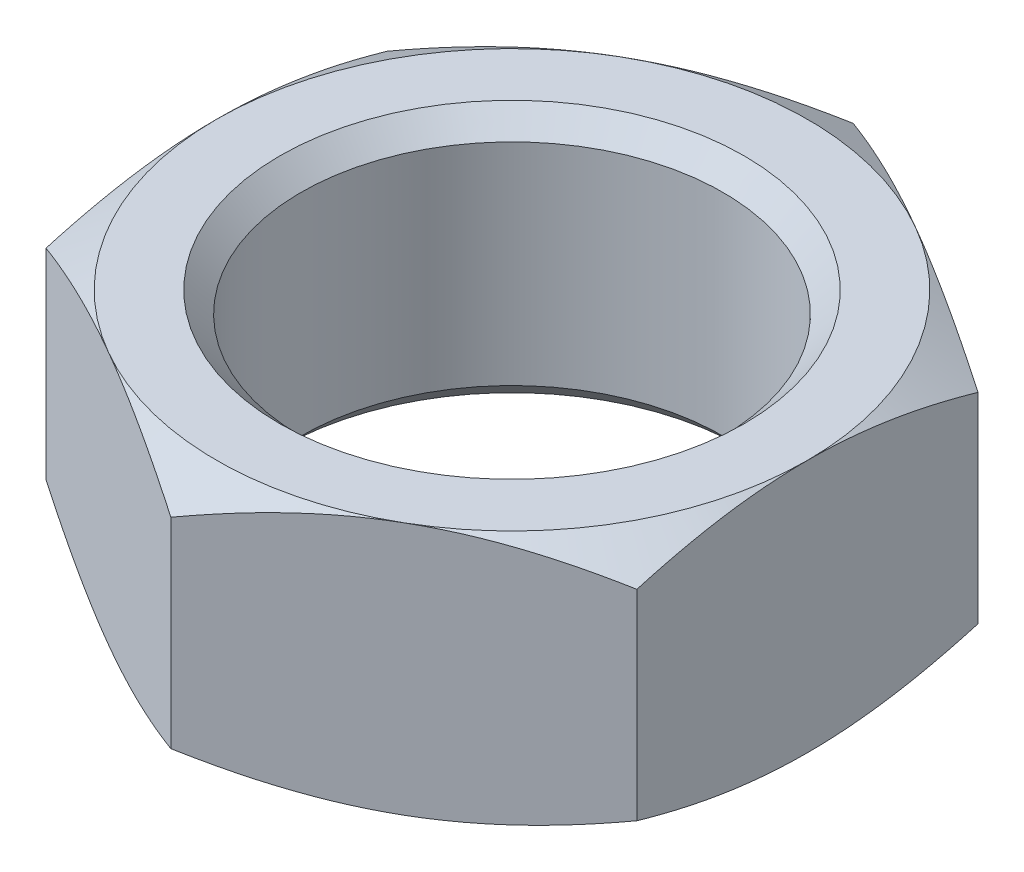
SolidWorks part; units mm, degrees
ref_plane "Front Plane" through (0, 0, 0) normal (0, 0, 1) x (1, 0, 0)
ref_plane "Top Plane" through (0, 0, 0) normal (0, 1, 0) x (1, 0, 0)
ref_plane "Right Plane" through (0, 0, 0) normal (1, 0, 0) x (0, 0, -1)
sketch "Sketch1" plane through (0, 0, 0) normal (0, 1, 0) x (1, 0, 0)
  line L1 (0, 16.1658) -> (-14, 8.0829)
  line L2 (-14, 8.0829) -> (-14, -8.0829)
  line L3 (-14, -8.0829) -> (0, -16.1658)
  line L4 (0, -16.1658) -> (14, -8.0829)
  line L5 (14, -8.0829) -> (14, 8.0829)
  line L6 (14, 8.0829) -> (0, 16.1658)
  circle A0 centre (0, 0) radius 14 construction
  point P1 (0, 0)
  dimension "D1" = 28
extrude "Boss-Extrude1" add sketch "Sketch1" along normal mid plane 12
sketch "Sketch2" plane through (0, 6, 0) normal (0, 1, 0) x (1, 0, 0)
  line L0 (14, 8.0829) -> (0, 16.1658) construction
  circle A0 centre (0, 0) radius 14
extrude "Cut-Extrude1" cut sketch "Sketch2" against normal blind 12 draft 60 flip side to cut
mirror "Mirror1" about plane through (0, 0, 0) normal (0, 1, 0) of "Cut-Extrude1"
sketch "Sketch3" plane through (0, 6, 0) normal (0, 1, 0) x (1, 0, 0)
  circle A0 centre (0, 0) radius 10
  dimension "D1" = 20
extrude "Cut-Extrude2" cut sketch "Sketch3" against normal through all
chamfer "Chamfer1" distance 1 angle 45 2 edges at (0, -6, 10) (0, 6, 10)
